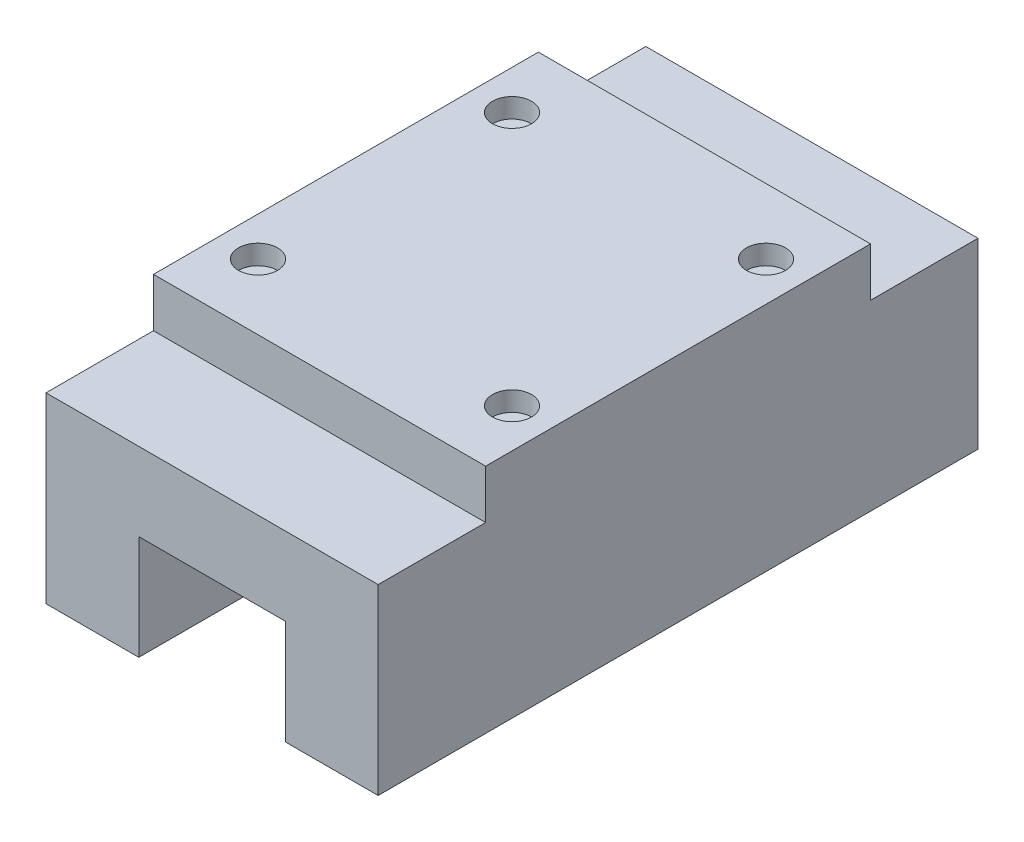
SolidWorks part; units mm, degrees
ref_plane "Спереди" through (0, 0, 0) normal (0, 0, 1) x (1, 0, 0)
ref_plane "Сверху" through (0, 0, 0) normal (0, 1, 0) x (1, 0, 0)
ref_plane "Справа" through (0, 0, 0) normal (1, 0, 0) x (0, 0, -1)
sketch "Эскиз1" plane through (0, 0, 0) normal (0, 0, 1) x (1, 0, 0)
  line L0 (24.5, 0) -> (34, 0)
  line L1 (0, 0) -> (9.5, 0)
  line L2 (0, 0) -> (0, 23.7)
  line L3 (0, 23.7) -> (34, 23.7)
  line L4 (34, 0) -> (34, 23.7)
  line L6 (9.5, 0) -> (9.5, 10.7)
  line L7 (9.5, 10.7) -> (24.5, 10.7)
  line L8 (24.5, 0) -> (24.5, 10.7)
  dimension "D1" = 23.7
  dimension "D2" = 34
  dimension "D3" = 10.7
  dimension "D4" = 15
  dimension "D5" = 9.5
extrude "Вытянуть1" add sketch "Эскиз1" along normal blind 61.4
sketch "Эскиз2" plane through (34, 0, 0) normal (1, 0, 0) x (0, 0, -1)
  line L0 (-50.4, 18.7) -> (-11, 18.7) construction
  line L1 (-50.4, 24.2476) -> (-68.3636, 24.2476)
  line L2 (-50.4, 24.2476) -> (-50.4, 18.7)
  line L3 (-50.4, 18.7) -> (-68.3636, 18.7)
  line L4 (-68.3636, 24.2476) -> (-68.3636, 18.7)
  line L5 (-11, 25.2567) -> (11.8104, 25.2567)
  line L6 (-11, 25.2567) -> (-11, 18.7)
  line L7 (-11, 18.7) -> (11.8104, 18.7)
  line L8 (11.8104, 25.2567) -> (11.8104, 18.7)
  line L9 (0, 0) -> (0, 23.7) construction
  line L11 (-61.4, 23.7) -> (0, 23.7) construction
  dimension "D1" = 39.4
  dimension "D2" = 11
  dimension "D3" = 5
extrude "Вырез-Вытянуть1" cut sketch "Эскиз2" against normal blind 61.4
sketch "Эскиз3" plane through (0, 23.7, 0) normal (0, 1, 0) x (-1, 0, 0)
  line L0 (-4.0002, 17.6999) -> (-30.0002, 17.6999) construction
  line L1 (-30.0002, 17.6999) -> (-30.0002, 43.6999) construction
  line L2 (-30.0002, 43.6999) -> (-4.0002, 43.6999) construction
  line L3 (-4.0002, 43.6999) -> (-4.0002, 17.6999) construction
  circle A0 centre (-4.0002, 17.6999) radius 2
  circle A1 centre (-30.0002, 17.6999) radius 2
  circle A2 centre (-4.0002, 43.6999) radius 2
  circle A3 centre (-30.0002, 43.6999) radius 2
  point P8 (-17.0002, 30.6999)
  point P9 (-17, 30.7)
  dimension "D1" = 26
  dimension "D2" = 26
  dimension "D3" = 0.0002
extrude "Вырез-Вытянуть2" cut sketch "Эскиз3" against normal blind 2
